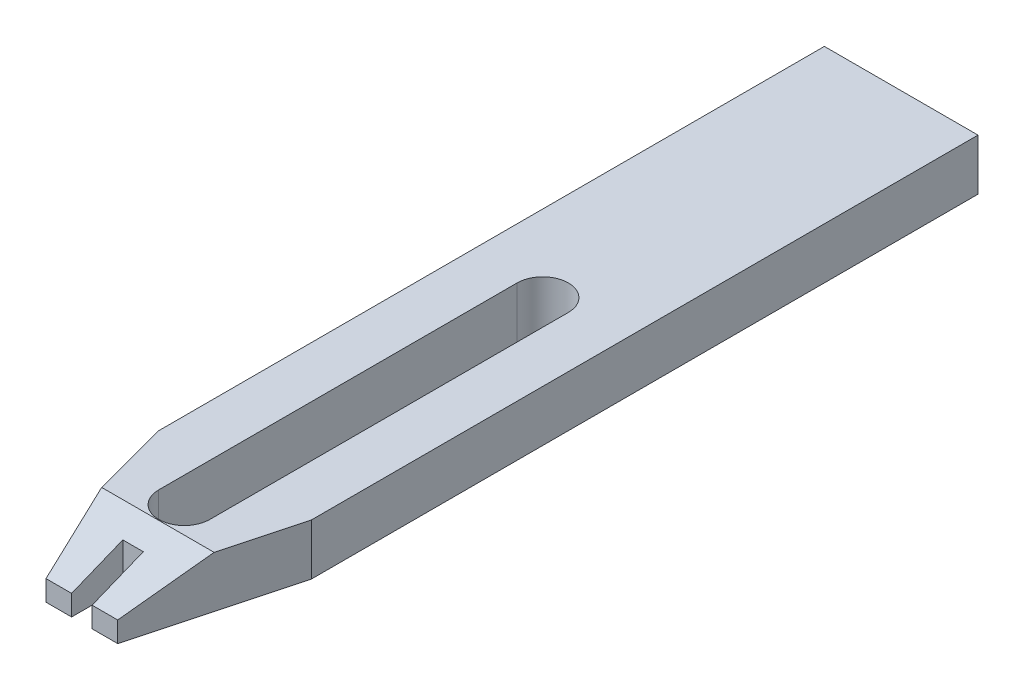
SolidWorks part; units mm, degrees
ref_plane "Front Plane" through (0, 0, 0) normal (0, 0, 1) x (1, 0, 0)
ref_plane "Top Plane" through (0, 0, 0) normal (0, 1, 0) x (1, 0, 0)
ref_plane "Right Plane" through (0, 0, 0) normal (1, 0, 0) x (0, 0, -1)
sketch "Sketch1" plane through (0, 0, 0) normal (0, 1, 0) x (1, 0, 0)
  line L0 (0, -30) -> (0, 5) construction
  line L1 (-7.5, 40) -> (7.5, 40)
  line L2 (-7.5, 40) -> (-7.5, -40)
  line L3 (-1, -40) -> (-7.5, -40)
  line L4 (7.5, 40) -> (7.5, -40)
  line L5 (-7.5, 40) -> (7.5, -40) construction
  line L6 (-7.5, -40) -> (7.5, 40) construction
  line L7 (-2.5, -30) -> (-2.5, 5)
  line L8 (2.5, -30) -> (2.5, 5)
  line L9 (-1, -40) -> (-1, -35)
  line L10 (-1, -35) -> (1, -35)
  line L11 (1, -35) -> (1, -40)
  line L12 (1, -40) -> (7.5, -40)
  arc A0 (-2.5, -30) -> (2.5, -30) centre (0, -30) ccw
  arc A1 (2.5, 5) -> (-2.5, 5) centre (0, 5) ccw
  point P0 (0, 0)
  point P8 (0, -12.5)
  dimension "D3" = 35
  dimension "D5" = 2
  dimension "D1" = 80
  dimension "D2" = 15
  dimension "D4" = 5
  dimension "D6" = 6.5
  dimension "D7" = 5
extrude "Boss-Extrude1" add sketch "Sketch1" along normal blind 5
chamfer "Chamfer1" distance 4 angle 75 2 edges at (-7.5, 2.5, 40) (7.5, 2.5, 40)
chamfer "Chamfer2" distance 3 angle 68 1 edges at (2.25, 5, 40)
